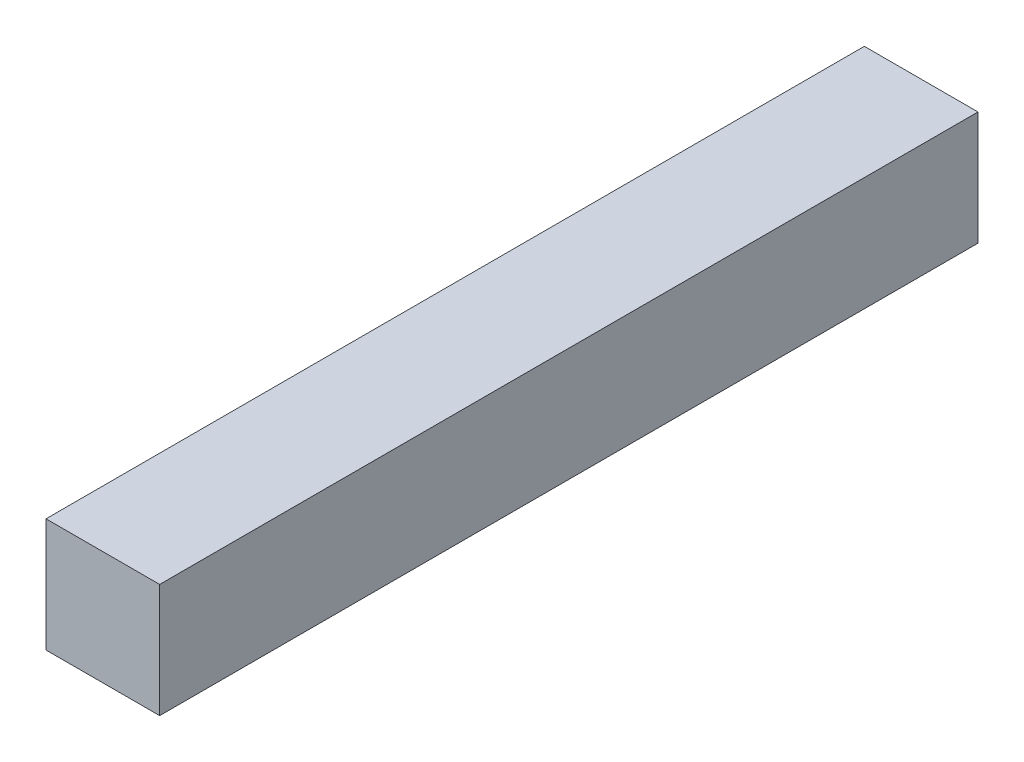
SolidWorks part; units mm, degrees
ref_plane "Front Plane" through (0, 0, 0) normal (0, 0, 1) x (1, 0, 0)
ref_plane "Top Plane" through (0, 0, 0) normal (0, 1, 0) x (1, 0, 0)
ref_plane "Right Plane" through (0, 0, 0) normal (1, 0, 0) x (0, 0, -1)
sketch "Sketch1" plane through (0, 0, 0) normal (0, 0, 1) x (1, 0, 0)
  line L1 (-2.5, -2.5) -> (2.5, -2.5)
  line L2 (-2.5, -2.5) -> (-2.5, 2.5)
  line L3 (-2.5, 2.5) -> (2.5, 2.5)
  line L4 (2.5, -2.5) -> (2.5, 2.5)
  line L5 (-2.5, -2.5) -> (2.5, 2.5) construction
  line L6 (-2.5, 2.5) -> (2.5, -2.5) construction
  point P0 (0, 0)
  dimension "D1" = 5
  dimension "D2" = 5
extrude "Boss-Extrude1" add sketch "Sketch1" along normal blind 36
